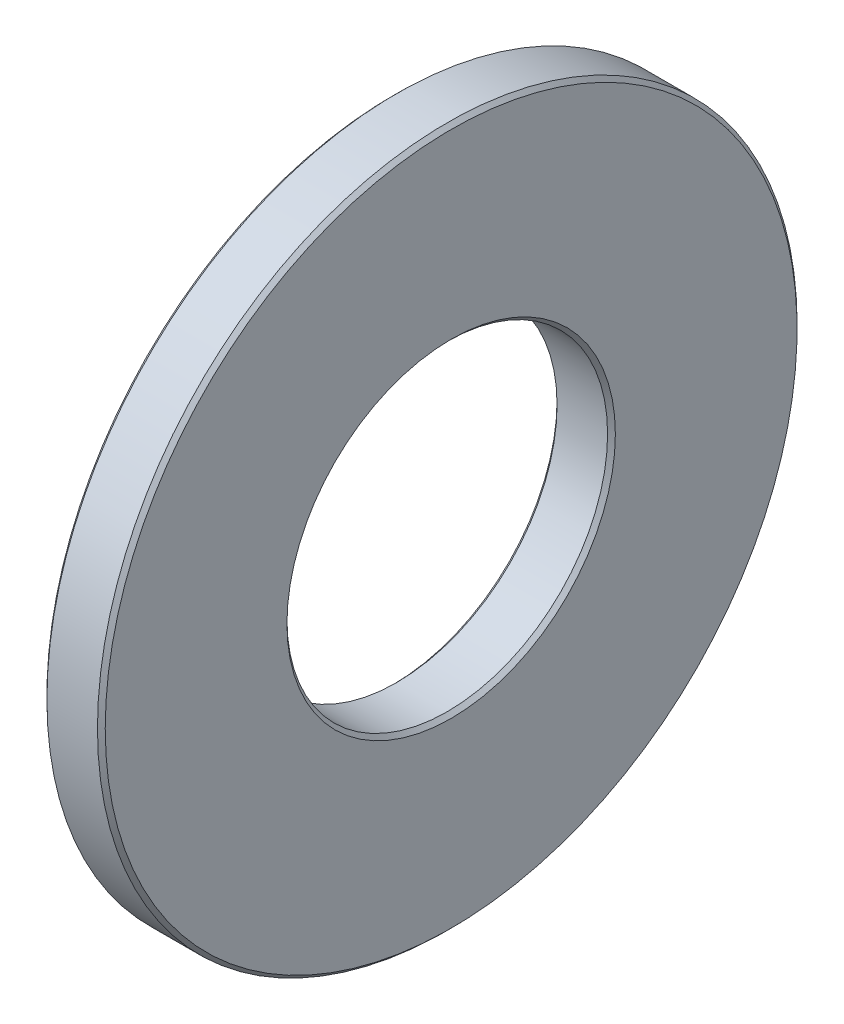
SolidWorks part; units mm, degrees
ref_plane "Face" through (0, 0, 0) normal (0, 0, 1) x (1, 0, 0)
ref_plane "Dessus" through (0, 0, 0) normal (0, 1, 0) x (1, 0, 0)
ref_plane "Droite" through (0, 0, 0) normal (1, 0, 0) x (0, 0, -1)
sketch "Esquisse1" plane through (0, 0, 0) normal (0, 0, 1) x (1, 0, 0)
  line L0 (0, 0) -> (20.1631, 0) construction
  line L2 (0, 4.125) -> (1.5, 4.125)
  line L3 (0, 4.125) -> (0, 9)
  line L4 (0, 9) -> (1.5, 9)
  line L5 (1.5, 4.125) -> (1.5, 9)
  dimension "D1" = 8.25
  dimension "D2" = 9
  dimension "D3" = 1.5
revolve "Base-Révolution" add sketch "Esquisse1" angle 360 about L0
chamfer "Chanfrein1" distance 0.1 angle 45
